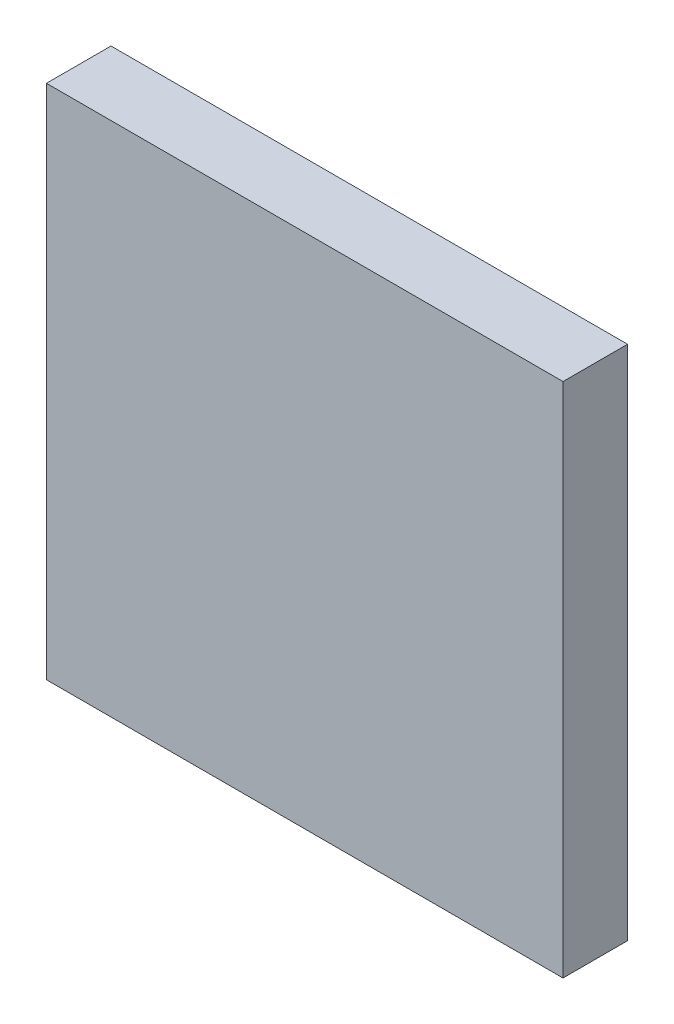
SolidWorks part; units mm, degrees
ref_plane "Alzado" through (0, 0, 0) normal (1, 0, 0) x (0, 1, 0)
ref_plane "Planta" through (0, 0, 0) normal (0, 0, 1) x (0, 1, 0)
ref_plane "Vista lateral" through (0, 0, 0) normal (0, 1, 0) x (-1, 0, 0)
sketch "Croquis1" plane through (0, 0, 0) normal (0, 0, 1) x (0, 1, 0)
  line L1 (-200, 200) -> (200, 200)
  line L2 (-200, 200) -> (-200, -200)
  line L3 (-200, -200) -> (200, -200)
  line L4 (200, 200) -> (200, -200)
  line L5 (-200, 200) -> (200, -200) construction
  line L6 (-200, -200) -> (200, 200) construction
  point P0 (0, 0)
  dimension "D1" = 400
  dimension "D2" = 400
extrude "Saliente-Extruir1" add sketch "Croquis1" along normal blind 50
